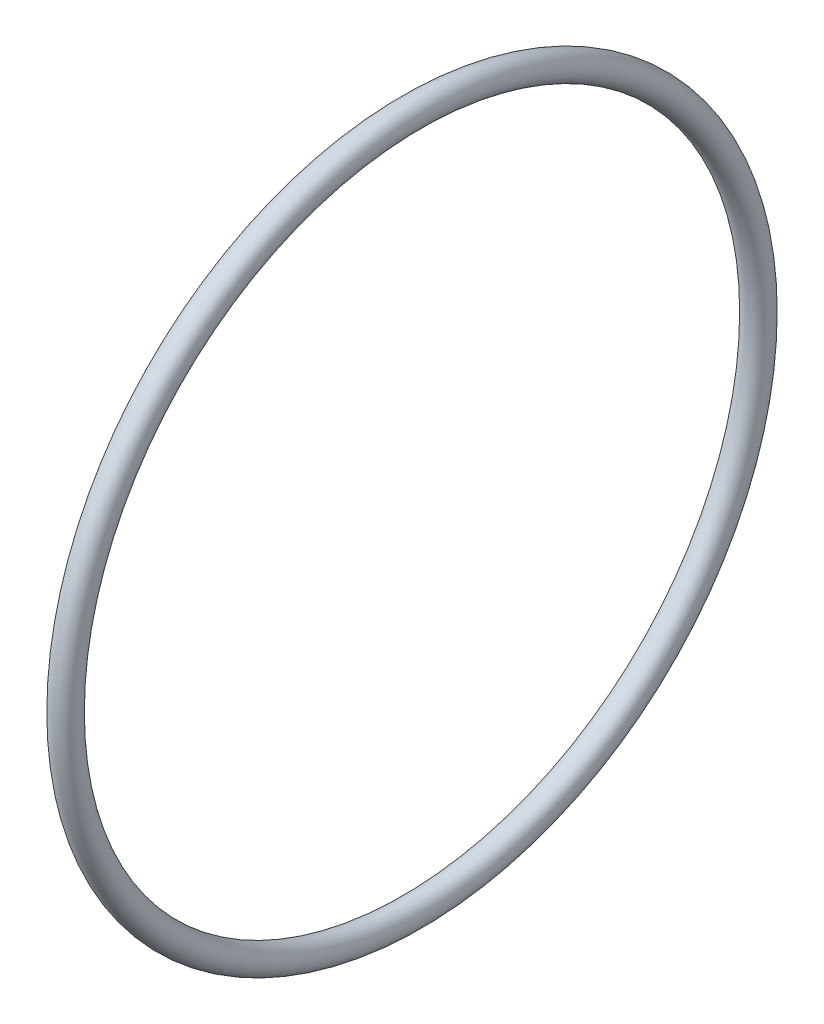
SolidWorks part; units mm, degrees
material "Rubber"
ref_plane "Front Plane" through (0, 0, 0) normal (0, 0, 1) x (1, 0, 0)
ref_plane "Top Plane" through (0, 0, 0) normal (0, 1, 0) x (1, 0, 0)
ref_plane "Right Plane" through (0, 0, 0) normal (1, 0, 0) x (0, 0, -1)
sketch "Sketch1" plane through (0, 0, 0) normal (1, 0, 0) x (0, 0, -1)
  circle A0 centre (0, 0) radius 41.402
  circle A1 centre (0, 0) radius 43.434
sweep "Sweep1" add path "Sketch1" circular profile diameter 3.175 parameters "D3"=3.175
